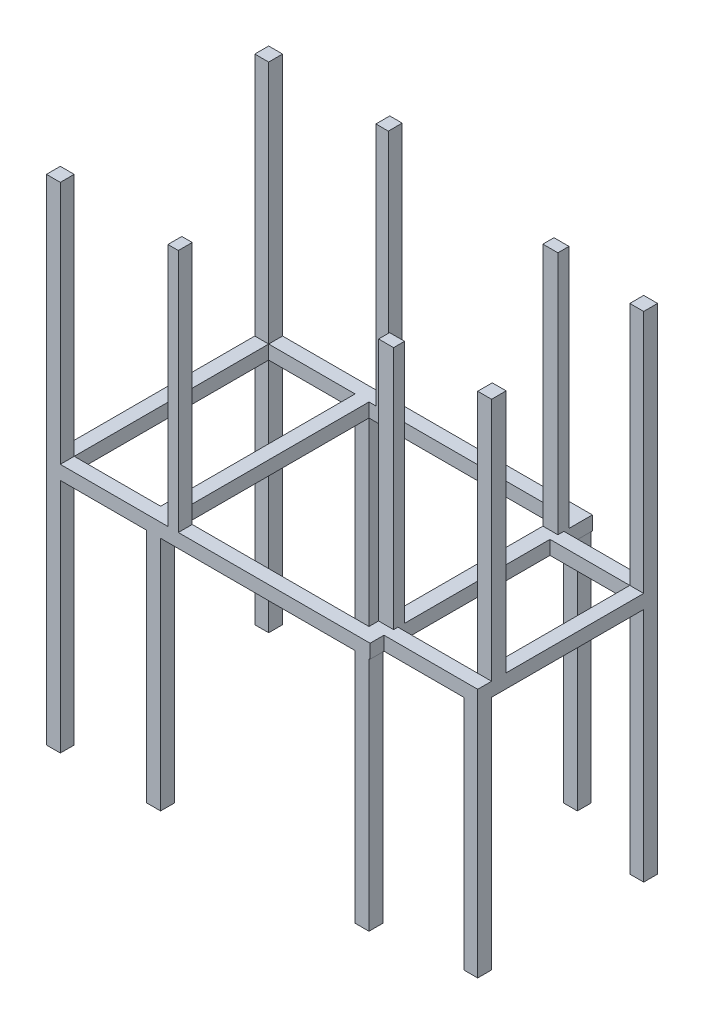
SolidWorks part; units mm, degrees
ref_plane "Alzado" through (0, 0, 0) normal (0, 0, 1) x (1, 0, 0)
ref_plane "Planta" through (0, 0, 0) normal (0, 1, 0) x (1, 0, 0)
ref_plane "Vista lateral" through (0, 0, 0) normal (1, 0, 0) x (0, 0, -1)
sketch "Croquis1" plane through (0, 0, 0) normal (0, 1, 0) x (1, 0, 0)
  line L0 (-50, 350) -> (-567.3891, 350) construction
  line L1 (0, 0) -> (700, 0)
  line L2 (0, 0) -> (0, 700)
  line L3 (0, 700) -> (700, 700)
  line L5 (-45.9557, -50) -> (754.0443, -50)
  line L17 (754.0443, 50) -> (1041.2481, 50)
  line L19 (-411.0383, 750) -> (-411.0383, -50)
  line L26 (-361.0383, 700) -> (-50, 700)
  line L27 (-361.0383, 700) -> (-361.0383, 0)
  line L28 (-361.0383, 0) -> (-50, 0)
  line L43 (1041.2481, 597.5553) -> (754.0443, 597.5553)
  line L47 (754.0443, 50) -> (754.0443, 597.5553)
  line L48 (-411.0383, 750) -> (-45.9557, 750)
  line L49 (-411.0383, -50) -> (-45.9557, -50)
  line L50 (-50, 0) -> (-50, 700)
  line L52 (1091.2481, 52.4447) -> (1091.2481, 647.5553)
  line L53 (1041.2481, 50) -> (1041.2481, 597.5553)
  line L54 (700, 0) -> (700, 700)
  line L55 (-45.9557, 750) -> (754.0443, 750)
  line L56 (754.0443, 750) -> (754.0443, 647.5553)
  line L57 (754.0443, 647.5553) -> (1091.2481, 647.5553)
  line L58 (754.0443, -50) -> (754.0443, 0)
  line L59 (754.0443, 0) -> (1091.2481, 0)
  line L60 (1091.2481, 0) -> (1091.2481, 52.4447)
  circle A0 centre (-167.3891, 350) radius 400 construction
  circle A1 centre (871.7891, 350) radius 300 construction
  dimension "D1" = 700
  dimension "D2" = 700
  dimension "D3" = 50
  dimension "D4" = 800
  dimension "D5" = 50
  dimension "D6" = 50
  dimension "D7" = 50
  dimension "D8" = 50
  dimension "D9" = 50
extrude "Saliente-Extruir1" add sketch "Croquis1" along normal blind 50
sketch "Croquis2" plane through (0, 0, 0) normal (0, -1, 0) x (1, 0, 0)
  line L0 (350, 0) -> (350, -700) construction
  line L1 (0, 0) -> (-50, 0)
  line L2 (0, 0) -> (0, 50)
  line L3 (0, 50) -> (-50, 50)
  line L4 (-50, 0) -> (-50, 50)
  line L5 (0, 0) -> (700, 0) construction
  line L6 (700, -700) -> (0, -700) construction
  line L7 (0, -350) -> (700, -350) construction
  line L8 (0, -700) -> (0, 0) construction
  line L9 (700, 0) -> (700, -700) construction
  line L10 (750, 0) -> (750, 50)
  line L11 (700, 50) -> (750, 50)
  line L12 (700, 0) -> (700, 50)
  line L13 (700, 0) -> (750, 0)
  line L14 (700, -700) -> (750, -700)
  line L15 (700, -700) -> (700, -750)
  line L16 (700, -750) -> (750, -750)
  line L17 (750, -700) -> (750, -750)
  line L18 (-50, -700) -> (-50, -750)
  line L19 (0, -750) -> (-50, -750)
  line L20 (0, -700) -> (0, -750)
  line L21 (0, -700) -> (-50, -700)
extrude "Saliente-Extruir2" add sketch "Croquis2" along normal blind 850
sketch "Croquis3" plane through (0, 50, 0) normal (0, 1, 0) x (1, 0, 0)
  line L0 (1041.2481, 50) -> (1041.2481, 597.5553) construction
  line L1 (-411.0383, 750) -> (-361.0383, 750)
  line L2 (-411.0383, 750) -> (-411.0383, 700)
  line L3 (-411.0383, 700) -> (-361.0383, 700)
  line L4 (-361.0383, 750) -> (-361.0383, 700)
  line L5 (1091.2481, 647.5553) -> (1041.2481, 647.5553)
  line L6 (1091.2481, 647.5553) -> (1091.2481, 597.5553)
  line L7 (1091.2481, 597.5553) -> (1041.2481, 597.5553)
  line L8 (1041.2481, 647.5553) -> (1041.2481, 597.5553)
  line L9 (1041.2481, 102.4447) -> (1091.2481, 102.4447)
  line L10 (1041.2481, 102.4447) -> (1041.2481, 50)
  line L11 (1041.2481, 50) -> (1091.2481, 50)
  line L12 (1091.2481, 102.4447) -> (1091.2481, 50)
  line L13 (1091.2481, 0) -> (1091.2481, 647.5553) construction
  line L14 (-361.0383, 700) -> (-361.0383, 0) construction
  line L15 (-361.0383, 0) -> (-411.0383, 0)
  line L16 (-361.0383, 0) -> (-361.0383, -50)
  line L17 (-361.0383, -50) -> (-411.0383, -50)
  line L18 (-411.0383, 0) -> (-411.0383, -50)
  line L19 (700, 700) -> (0, 700) construction
  line L20 (24.8421, 700) -> (69.5772, 700)
  line L21 (24.8421, 700) -> (24.8421, 750)
  line L22 (24.8421, 750) -> (69.5772, 750)
  line L23 (69.5772, 700) -> (69.5772, 750)
  line L24 (754.0443, 750) -> (-411.0383, 750) construction
  line L25 (0, 0) -> (700, 0) construction
  line L26 (26.26, 0) -> (63.7986, 0)
  line L27 (26.26, 0) -> (26.26, -50)
  line L28 (26.26, -50) -> (63.7986, -50)
  line L29 (63.7986, 0) -> (63.7986, -50)
  line L30 (-411.0383, -50) -> (754.0443, -50) construction
  line L31 (754.0443, 597.5553) -> (754.0443, 50) construction
  line L32 (754.0443, 74.0721) -> (700, 74.0721)
  line L33 (754.0443, 74.0721) -> (754.0443, 34.5533)
  line L34 (754.0443, 34.5533) -> (700, 34.5533)
  line L35 (700, 74.0721) -> (700, 34.5533)
  line L36 (700, 0) -> (700, 700) construction
  line L38 (754.0443, 625.9279) -> (700, 625.9279)
  line L39 (754.0443, 625.9279) -> (754.0443, 665.8797)
  line L40 (754.0443, 665.8797) -> (700, 665.8797)
  line L41 (700, 625.9279) -> (700, 665.8797)
  circle A0 centre (871.7891, 350) radius 300 construction
  circle A1 centre (-167.3891, 350) radius 400 construction
extrude "Saliente-Extruir3" add sketch "Croquis3" along normal up to surface (879.0597 mm away)
sketch "Croquis4" plane through (0, 0, 0) normal (0, -1, 0) x (1, 0, 0)
  line L1 (-411.0383, 50) -> (-361.0383, 50)
  line L2 (-411.0383, 50) -> (-411.0383, 0)
  line L3 (-411.0383, 0) -> (-361.0383, 0)
  line L4 (-361.0383, 50) -> (-361.0383, 0)
  line L5 (-411.0383, -750) -> (-361.0383, -750)
  line L6 (-411.0383, -750) -> (-411.0383, -700)
  line L7 (-411.0383, -700) -> (-361.0383, -700)
  line L8 (-361.0383, -750) -> (-361.0383, -700)
  line L9 (1091.2481, -647.5553) -> (1041.2481, -647.5553)
  line L10 (1091.2481, -647.5553) -> (1091.2481, -597.5553)
  line L11 (1091.2481, -597.5553) -> (1041.2481, -597.5553)
  line L12 (1041.2481, -647.5553) -> (1041.2481, -597.5553)
  line L13 (1091.2481, 0) -> (1041.2481, 0)
  line L14 (1091.2481, 0) -> (1091.2481, -50)
  line L15 (1091.2481, -50) -> (1041.2481, -50)
  line L16 (1041.2481, 0) -> (1041.2481, -50)
extrude "Saliente-Extruir4" add sketch "Croquis4" along normal blind 850
